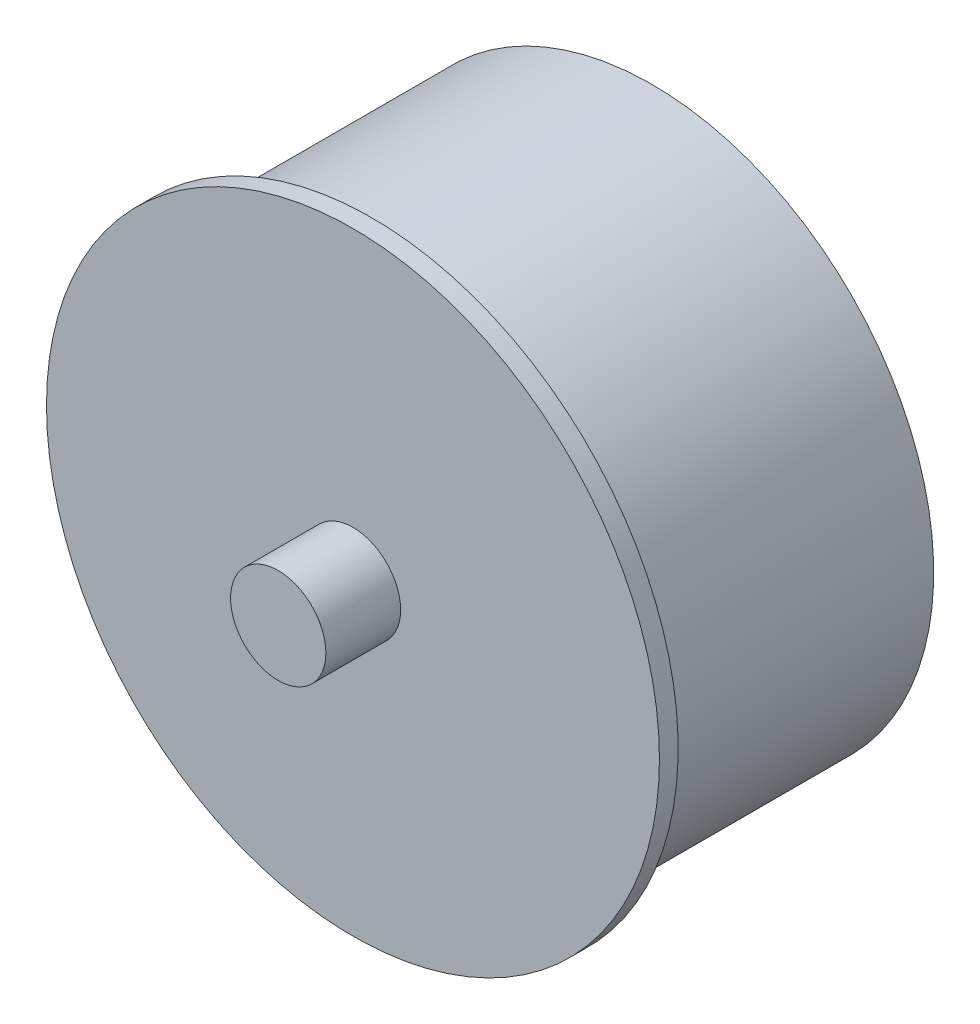
SolidWorks part; units mm, degrees
ref_plane "前视基准面" through (0, 0, 0) normal (0, 0, 1) x (1, 0, 0)
ref_plane "上视基准面" through (0, 0, 0) normal (0, 1, 0) x (1, 0, 0)
ref_plane "右视基准面" through (0, 0, 0) normal (1, 0, 0) x (0, 0, -1)
other "Configuration Table"
sketch "草图1" plane through (0, 0, 0) normal (0, 0, 1) x (1, 0, 0)
  circle A0 centre (0, 0) radius 16.4
  dimension "D1" = 32.8
extrude "凸台-拉伸1" add sketch "草图1" along normal blind 16
sketch "草图2" plane through (0, 0, 16) normal (0, 0, 1) x (1, 0, 0)
  circle A0 centre (0, 0) radius 2.55
  dimension "D1" = 5.1
extrude "凸台-拉伸2" add sketch "草图2" along normal blind 4
sketch "草图3" plane through (0, 0, 0) normal (0, 0, -1) x (-1, 0, 0)
  circle A0 centre (0, 0) radius 10.075
  dimension "D1" = 20.15
extrude "凸台-拉伸3" add sketch "草图3" along normal blind 3 separate body
sketch "草图5" plane through (0, 0, 0) normal (0, 0, -1) x (-1, 0, 0)
  circle A0 centre (0, 0) radius 15.075
  circle A1 centre (0, 0) radius 16.4
extrude "切除-拉伸2" cut sketch "草图5" against normal blind 15
sketch "草图7" plane through (0, 0, -3) normal (0, 0, -1) x (-1, 0, 0)
  line L0 (0, 0) -> (0, 8) construction
  line L1 (0, 0) -> (8, 0) construction
  line L2 (0, 0) -> (0, -8) construction
  line L3 (0, 0) -> (-8, 0) construction
  circle A0 centre (0, 8) radius 1.05
  circle A1 centre (8, 0) radius 1.05
  circle A2 centre (0, -8) radius 1.05
  circle A3 centre (-8, 0) radius 1.05
  point P13 (0, 0)
  dimension "D1" = 4
extrude "切除-拉伸3" cut sketch "草图7" against normal blind 10 contours A0 | A1 | A2 | A3
